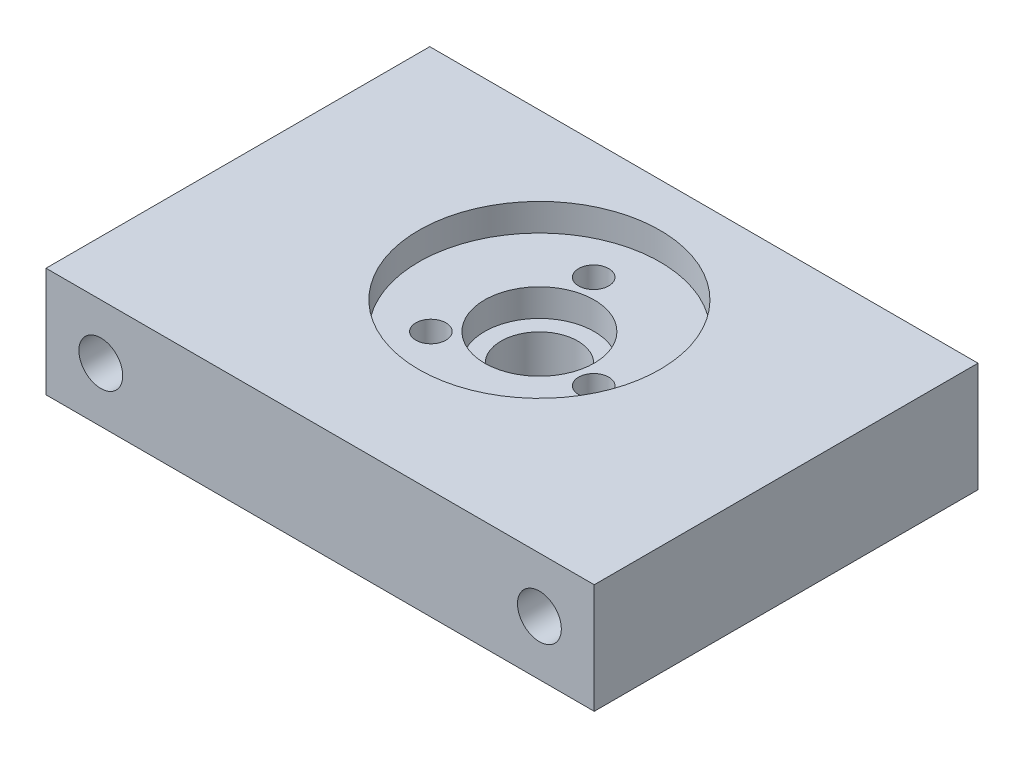
SolidWorks part; units mm, degrees
material "PVC rigide"
ref_plane "Plan de face" through (0, 0, 0) normal (0, 0, 1) x (1, 0, 0)
ref_plane "Plan de dessus" through (0, 0, 0) normal (0, 1, 0) x (1, 0, 0)
ref_plane "Plan de droite" through (0, 0, 0) normal (1, 0, 0) x (0, 0, -1)
sketch "Esquisse1" plane through (0, 0, 0) normal (0, 1, 0) x (1, 0, 0)
  line L1 (-25, 17.5) -> (25, 17.5)
  line L2 (-25, 17.5) -> (-25, -17.5)
  line L3 (-25, -17.5) -> (25, -17.5)
  line L4 (25, 17.5) -> (25, -17.5)
  line L5 (-25, -17.5) -> (25, 17.5) construction
  line L6 (25, -17.5) -> (-25, 17.5) construction
  point P4 (0, 0)
  dimension "D1" = 50
  dimension "D2" = 35
extrude "Boss.-Extru.1" add sketch "Esquisse1" along normal blind 10
sketch "Esquisse2" plane through (0, 10, 0) normal (0, 1, 0) x (1, 0, 0)
  line L1 (-25, 17.5) -> (25, 17.5) construction
  line L2 (0, 17.5) -> (0, -17.5) construction
  line L3 (25, 17.5) -> (-25, 17.5) construction
  line L4 (-25, -17.5) -> (25, -17.5) construction
  circle A0 centre (0, 2.5) radius 5
  dimension "D2" = 10
  dimension "D1" = 15
extrude "Enlèv. mat.-Extru.1" cut sketch "Esquisse2" against normal blind 5
sketch "Esquisse3" plane through (0, 10, 0) normal (0, 1, 0) x (1, 0, 0)
  line L0 (-4.9497, -2.4497) -> (-1.8117, 9.2615) construction
  line L1 (-1.8117, 9.2615) -> (6.7615, 0.6883) construction
  line L2 (6.7615, 0.6883) -> (-4.9497, -2.4497) construction
  line L3 (0, 2.5) -> (-1.8117, 9.2615) construction
  line L5 (0, -17.5) -> (0, 17.5) construction
  line L6 (-25, -17.5) -> (25, -17.5) construction
  line L7 (25, 17.5) -> (-25, 17.5) construction
  circle A0 centre (0, 2.5) radius 7 construction
  circle A1 centre (-1.8117, 9.2615) radius 1.375
  circle A2 centre (6.7615, 0.6883) radius 1.375
  circle A3 centre (-4.9497, -2.4497) radius 1.375
  circle A4 centre (0, 2.5) radius 3.5
  dimension "D1" = 14
  dimension "D2" = 2.75
  dimension "D3" = 7
  dimension "D4" = 15
extrude "Enlèv. mat.-Extru.2" cut sketch "Esquisse3" against normal blind 15
sketch "Esquisse4" plane through (0, 10, 0) normal (0, 1, 0) x (1, 0, 0)
  circle A0 centre (0, 2.5) radius 11
  dimension "D1" = 22
extrude "Enlèv. mat.-Extru.3" cut sketch "Esquisse4" against normal blind 2.5
sketch "Esquisse5" plane through (0, 0, 0) normal (0, -1, 0) x (1, 0, 0)
  circle A0 centre (-4.9497, 2.4497) radius 2.25
  circle A1 centre (6.7615, -0.6883) radius 2.25
  circle A2 centre (-1.8117, -9.2615) radius 2.25
  dimension "D1" = 4.5
extrude "Enlèv. mat.-Extru.4" cut sketch "Esquisse5" against normal blind 2.5
sketch "Esquisse6" plane through (0, 0, 17.5) normal (0, 0, 1) x (1, 0, 0)
  line L0 (-25, 5) -> (25, 5) construction
  line L1 (-25, 10) -> (-25, 0) construction
  line L2 (25, 10) -> (25, 0) construction
  circle A0 centre (-20, 5) radius 2
  circle A1 centre (20, 5) radius 2
  dimension "D1" = 4
  dimension "D2" = 5
  dimension "D3" = 5
extrude "Enlèv. mat.-Extru.5" cut sketch "Esquisse6" against normal blind 10
